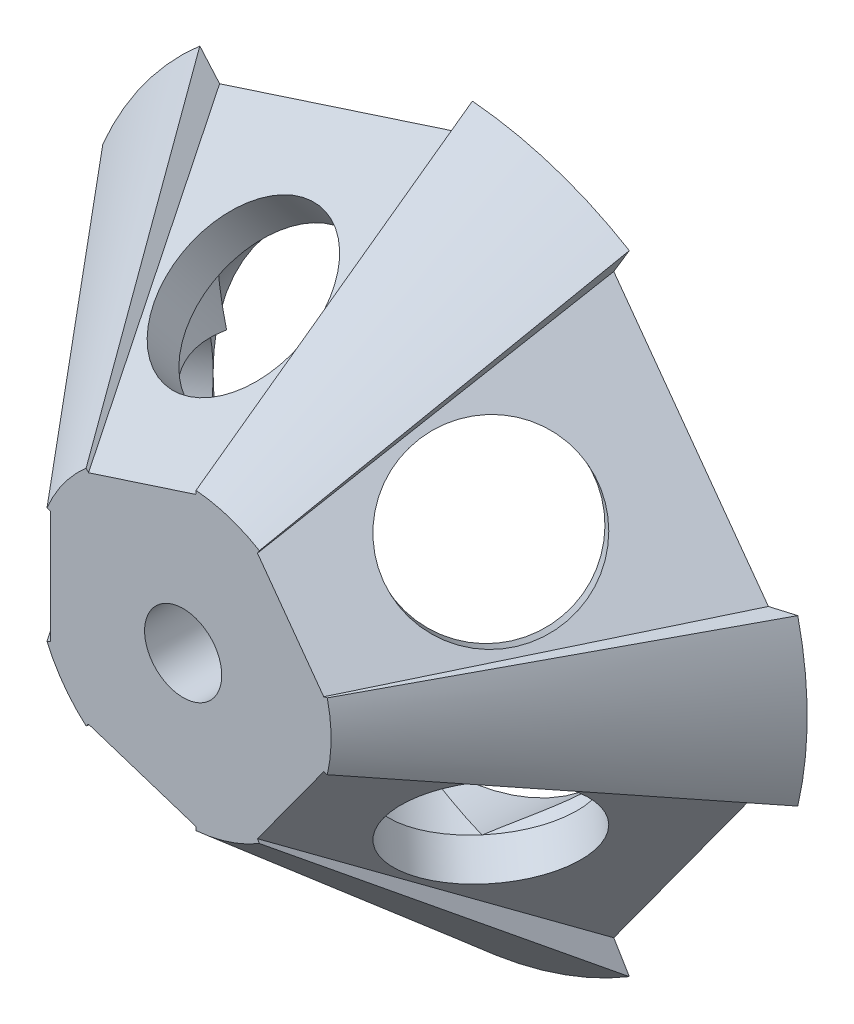
SolidWorks part; units mm, degrees
ref_plane "Front Plane" through (0, 0, 0) normal (0, 0, 1) x (1, 0, 0)
ref_plane "Top Plane" through (0, 0, 0) normal (0, 1, 0) x (1, 0, 0)
ref_plane "Right Plane" through (0, 0, 0) normal (1, 0, 0) x (0, 0, -1)
sketch "Sketch2" plane through (0, 0, 0) normal (0, 0, 1) x (1, 0, 0)
  line L0 (9.2003, -28.3156) -> (29.7728, 0)
  line L1 (29.7728, 0) -> (9.2003, 28.3156)
  line L2 (9.2003, 28.3156) -> (-24.0867, 17.5)
  line L3 (-24.0867, 17.5) -> (-24.0867, -17.5)
  line L4 (-24.0867, -17.5) -> (9.2003, -28.3156)
  circle A0 centre (0, 0) radius 24.0867 construction
  dimension "D1" = 35
ref_plane "Plane1" through (0, 0, 20) normal (0, 0, 1) x (1, 0, 0)
sketch "Sketch3" plane through (0, 0, 20) normal (0, 0, 1) x (1, 0, 0)
  line L1 (-10.3229, 7.5) -> (-10.3229, -7.5)
  line L2 (-10.3229, -7.5) -> (3.943, -12.1353)
  line L3 (3.943, -12.1353) -> (12.7598, 0)
  line L4 (12.7598, 0) -> (3.943, 12.1353)
  line L5 (3.943, 12.1353) -> (-10.3229, 7.5)
  circle A0 centre (0, 0) radius 10.3229 construction
  dimension "D1" = 15
loft "Loft1" add profiles "Sketch2", "Sketch3"
sketch "Sketch4" plane through (-16.3454, 0, 11.2488) normal (-0.8238, 0, 0.5669) x (0.5669, 0, 0.8238)
  line L0 (15.6453, 0) -> (-15.6453, 0) construction
  line L1 (-13.6551, 0) -> (10.6233, 0) construction
  line L2 (-13.6551, 17.5) -> (-13.6551, -17.5) construction
  line L3 (10.6233, 7.5) -> (10.6233, -7.5) construction
  line L4 (-1.5159, 0) -> (-1.5159, 3.0914) construction
  circle A0 centre (-1.5159, 0) radius 6.5
  dimension "D1" = 13
extrude "Cut-Extrude1" cut sketch "Sketch4" against normal blind 30
ref_axis "Axis1" through (0, 0, 31.5001) along (0, 0, -1)
sketch "Sketch5" plane through (0, 0, 0) normal (0, 0, -1) x (-1, 0, 0)
  circle A0 centre (0, 0) radius 5
  dimension "D1" = 10
extrude "Cut-Extrude2" cut sketch "Sketch5" against normal blind 12
sketch "Sketch10" plane through (0, 0, 0) normal (0, 0, -1) x (-1, 0, 0)
  circle A0 centre (0, 0) radius 17.6737
extrude "Cut-Extrude4" cut sketch "Sketch10" against normal blind 5
pattern_circular "CirPattern1" count 5 over 360 about axis through (0, 0, 31.5001) along (0, 0, -1) of "Cut-Extrude1"
ref_axis "Axis2" through (-2.7508, 0, 0.0529) along (-0.8238, 0, 0.5669)
sketch "Sketch6" plane through (0, 0, 0) normal (0, 1, 0) x (1, 0, 0)
  line L0 (0.1954, -8.3437) -> (-9.9147, -15.3014)
  line L1 (-9.9147, -15.3014) -> (-11.5833, -12.8767)
  line L2 (-11.5833, -12.8767) -> (-4.8964, -8.2749)
  line L3 (-4.8964, -8.2749) -> (0.1954, -8.3437)
  line L4 (-2.7508, -0.0529) -> (-46.1725, -29.9353) construction
  line L5 (-24.0867, 0) -> (-10.3229, -20) construction
  dimension "D1" = 3
  dimension "D2" = 8.5
revolve "Cut-Revolve1" cut sketch "Sketch6" angle 360 about axis through (-2.7508, 0, 0.0529) along (-0.8238, 0, 0.5669)
pattern_circular "CirPattern2" count 5 every 72 about axis through (0, 0, 0) along (0, 0, 1) of "Cut-Revolve1"
sketch "Sketch7" plane through (0, 0, 20) normal (0, 0, 1) x (1, 0, 0)
  circle A0 centre (0, 0) radius 3
  dimension "D1" = 6
extrude "Cut-Extrude3" cut sketch "Sketch7" against normal blind 20
sketch "Sketch9" plane through (0, 0, 0) normal (0, 1, 0) x (1, 0, 0)
  line L1 (28.513, 0) -> (11.5, -20)
  line L2 (12.7598, -20) -> (3.943, -20) construction
  line L3 (29.7728, 0) -> (9.2003, 0) construction
  line L4 (29.7728, 0) -> (12.7598, -20) construction
  line L6 (0, -31.5001) -> (0, 15.6849) construction
  line L7 (11.5, -20) -> (21.5029, -41.2741)
  line L8 (21.5029, -41.2741) -> (58.576, -6.2991)
  line L9 (58.576, -6.2991) -> (42.0048, 5.1067)
  line L10 (42.0048, 5.1067) -> (28.513, 0)
  dimension "D1" = 11.5
revolve "Cut-Revolve2" cut sketch "Sketch9" angle 360 about axis through (0, 0, 31.5001) along (0, 0, -1)
sketch "Sketch11" plane through (0, 0, 0) normal (0, 1, 0) x (1, 0, 0)
  line L0 (11.5, -20) -> (28.513, 0)
  line L3 (11.5, -20) -> (8.0219, -20)
  line L4 (5.3723, -20) -> (11.3305, -20) construction
  line L5 (8.0219, -20) -> (25.0349, 0)
  line L6 (10.5178, 0) -> (28.4553, 0) construction
  line L7 (25.0349, 0) -> (28.513, 0)
  line L8 (0, 0) -> (0, -25.1397) construction
  dimension "D1" = 11.5
revolve "Revolve1" add sketch "Sketch11" angle 26 mid plane about L8
pattern_circular "CirPattern3" count 5 every 72 about axis through (0, 0, 0) along (0, 0, 1) of "Revolve1"
